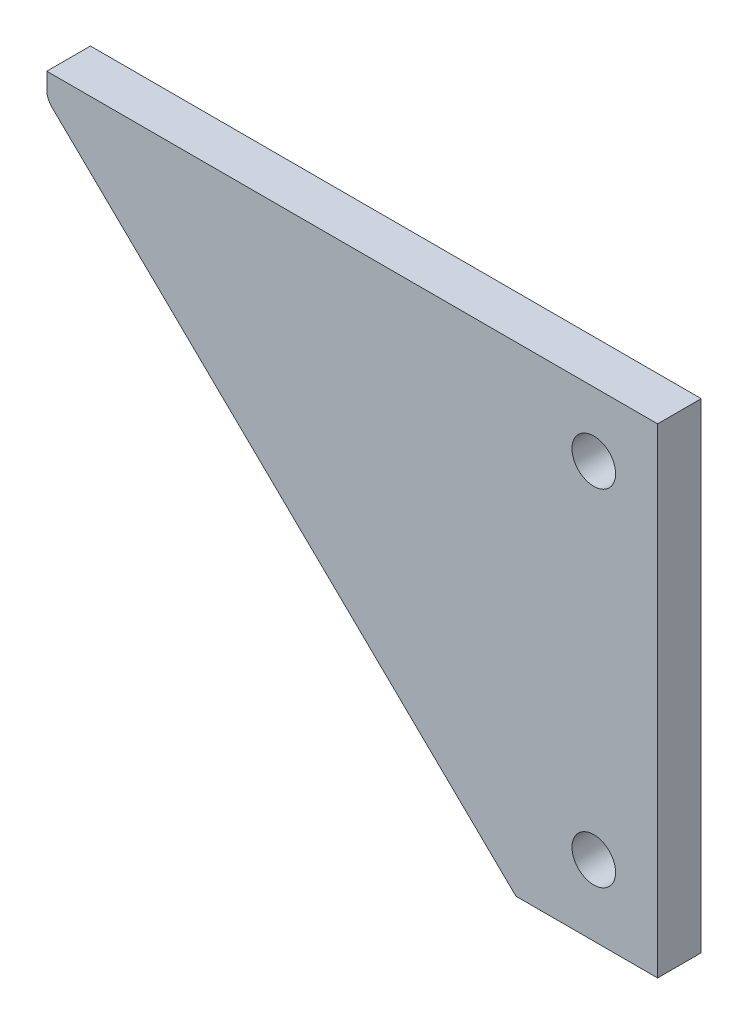
SolidWorks part; units mm, degrees
ref_plane "Plan de face" through (0, 0, 0) normal (0, 0, 1) x (1, 0, 0)
ref_plane "Plan de dessus" through (0, 0, 0) normal (0, 1, 0) x (1, 0, 0)
ref_plane "Plan de droite" through (0, 0, 0) normal (1, 0, 0) x (0, 0, -1)
sketch "Esquisse1" plane through (0, 0, 0) normal (0, 0, 1) x (1, 0, 0)
  line L0 (-39.7519, 27.4031) -> (30.2481, 27.4031)
  line L1 (30.2481, 27.4031) -> (30.2481, -27.5969)
  line L2 (30.2481, -27.5969) -> (14.017, -27.5969)
  line L3 (14.017, -27.5969) -> (-39.7519, 24.6899)
  line L4 (-39.7519, 24.6899) -> (-39.7519, 27.4031)
  line L5 (22.9363, 34.2761) -> (22.9363, -40.3185) construction
  circle A0 centre (22.9363, 20.0453) radius 2.5
  circle A1 centre (22.9363, -19.5196) radius 2.5
  dimension "D4" = 5
  dimension "D5" = 5
  dimension "D1" = 70
  dimension "D2" = 75
  dimension "D3" = 55
extrude "Boss.-Extru.2" add sketch "Esquisse1" along normal blind 5
fillet "Congé2" radius 2 1 edges at (-39.7519, 24.6899, 2.5)
